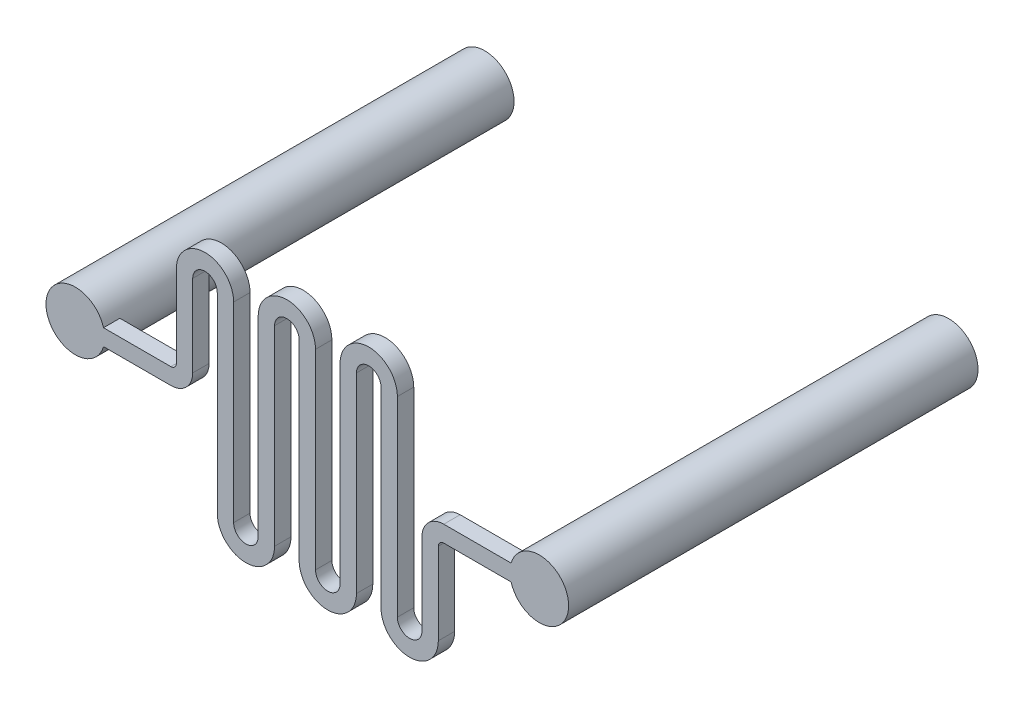
SolidWorks part; units mm, degrees
ref_plane "Front Plane" through (0, 0, 0) normal (0, 0, 1) x (1, 0, 0)
ref_plane "Top Plane" through (0, 0, 0) normal (0, 1, 0) x (1, 0, 0)
ref_plane "Right Plane" through (0, 0, 0) normal (1, 0, 0) x (0, 0, -1)
sketch "Sketch2" plane through (0, 0, 0) normal (0, 0, 1) x (1, 0, 0)
  line L3 (-20.5, -0.6) -> (-13.5, -0.6)
  line L6 (-11.9, 1) -> (-11.9, 7)
  line L9 (-10.1, 7) -> (-10.1, 0)
  line L12 (-10.1, 0) -> (-10.1, -7)
  line L15 (-5.9, -7) -> (-5.9, 0)
  line L18 (-5.9, 0) -> (-5.9, 7)
  line L21 (-4.1, 7) -> (-4.1, 0)
  line L22 (-4.1, 0) -> (-4.1, -7)
  line L23 (0.1, -7) -> (0.1, 0)
  line L24 (0.1, 0) -> (0.1, 7)
  line L25 (1.9, 7) -> (1.9, 0)
  line L26 (1.9, 0) -> (1.9, -7)
  line L27 (6.1, -7) -> (6.1, -1)
  line L28 (6.5, -0.6) -> (13.5, -0.6)
  line L29 (-20.5, 0.6) -> (-13.5, 0.6)
  line L30 (-13.1, 1) -> (-13.1, 7)
  line L31 (-8.9, 7) -> (-8.9, 0)
  line L32 (-8.9, 0) -> (-8.9, -7)
  line L33 (-7.1, -7) -> (-7.1, 0)
  line L34 (-7.1, 0) -> (-7.1, 7)
  line L35 (-2.9, 7) -> (-2.9, 0)
  line L36 (-2.9, 0) -> (-2.9, -7)
  line L37 (-1.1, -7) -> (-1.1, 0)
  line L38 (-1.1, 0) -> (-1.1, 7)
  line L39 (3.1, 7) -> (3.1, 0)
  line L40 (3.1, 0) -> (3.1, -7)
  line L41 (4.9, -7) -> (4.9, -1)
  line L42 (6.5, 0.6) -> (13.5, 0.6)
  arc A0 (-20.5, 0.6) -> (-20.5, -0.6) centre (-20.5, 0) ccw
  arc A1 (13.5, -0.6) -> (13.5, 0.6) centre (13.5, 0) ccw
  arc A8 (-11.9, 1) -> (-13.5, -0.6) centre (-13.5, 1) cw
  arc A9 (-11.9, 7) -> (-10.1, 7) centre (-11, 7) cw
  arc A10 (-10.1, -7) -> (-5.9, -7) centre (-8, -7) ccw
  arc A11 (-5.9, 7) -> (-4.1, 7) centre (-5, 7) cw
  arc A12 (-4.1, -7) -> (0.1, -7) centre (-2, -7) ccw
  arc A13 (0.1, 7) -> (1.9, 7) centre (1, 7) cw
  arc A14 (1.9, -7) -> (6.1, -7) centre (4, -7) ccw
  arc A15 (6.1, -1) -> (6.5, -0.6) centre (6.5, -1) cw
  arc A16 (-13.1, 1) -> (-13.5, 0.6) centre (-13.5, 1) cw
  arc A17 (-13.1, 7) -> (-8.9, 7) centre (-11, 7) cw
  arc A18 (-8.9, -7) -> (-7.1, -7) centre (-8, -7) ccw
  arc A19 (-7.1, 7) -> (-2.9, 7) centre (-5, 7) cw
  arc A20 (-2.9, -7) -> (-1.1, -7) centre (-2, -7) ccw
  arc A21 (-1.1, 7) -> (3.1, 7) centre (1, 7) cw
  arc A22 (3.1, -7) -> (4.9, -7) centre (4, -7) ccw
  arc A23 (4.9, -1) -> (6.5, 0.6) centre (6.5, -1) cw
  point P4 (0, 0)
  point P32 (5.5, 0)
  point P35 (-12.5, 0)
  dimension "D1" = 8
extrude "Boss-Extrude1" add sketch "Sketch2" along normal blind 1.2
ref_plane "Plane1" through (0, 0, 0) normal (0, 1, 0) x (1, 0, 0)
sketch "Sketch3" plane through (0, 0, 0) normal (0, 1, 0) x (1, 0, 0)
  line L1 (-20.5, 28.8) -> (-22.65, 28.8)
  line L2 (-20.5, -1.2) -> (-20.5, 28.8)
  line L6 (-22.65, 28.8) -> (-22.65, -1.2)
  line L7 (-22.65, -1.2) -> (-20.5, -1.2)
  dimension "D1" = 2.15
  dimension "D3" = 30
ref_plane "Plane2" through (0, 0, 0) normal (0, 1, 0) x (1, 0, 0)
sketch "Sketch4" plane through (0, 0, 0) normal (0, 1, 0) x (1, 0, 0)
  line L1 (13.5, 28.8) -> (15.65, 28.8)
  line L2 (13.5, -1.2) -> (13.5, 28.8)
  line L6 (15.65, 28.8) -> (15.65, -1.2)
  line L7 (15.65, -1.2) -> (13.5, -1.2)
  dimension "D1" = 2.15
  dimension "D3" = 30
revolve "Revolve1" add sketch "Sketch3" angle 360 about L2
revolve "Revolve2" add sketch "Sketch4" angle 360 about L2
sketch "Sketch5" plane through (0, 0, -28.8) normal (0, 0, -1) x (-1, 0, 0)
  circle A0 centre (-13.5, 0) radius 1.5
  circle A1 centre (20.5, 0) radius 1.5
  dimension "D1" = 3
  dimension "D2" = 3
extrude "Cut-Extrude1" cut sketch "Sketch5" against normal blind 28
